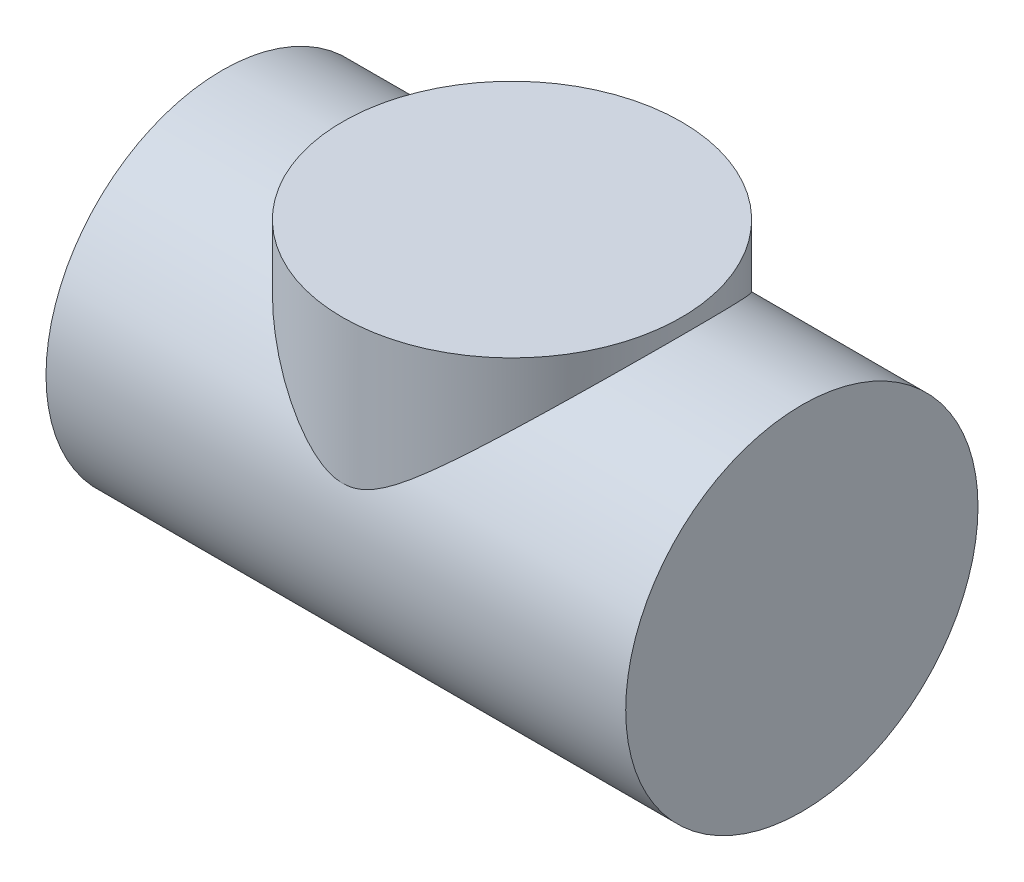
SolidWorks part; units mm, degrees
ref_plane "Front Plane" through (0, 0, 0) normal (0, 0, 1) x (1, 0, 0)
ref_plane "Top Plane" through (0, 0, 0) normal (0, 1, 0) x (1, 0, 0)
ref_plane "Right Plane" through (0, 0, 0) normal (1, 0, 0) x (0, 0, -1)
sketch "Sketch1" plane through (0, 0, 0) normal (1, 0, 0) x (0, 0, -1)
  circle A0 centre (0, 0) radius 0.0395
extrude "Boss-Extrude1" add sketch "Sketch1" along normal blind 0.13 from offset 0.065 offset against normal yes
sketch "Sketch2" plane through (0, 0, 0) normal (0, 1, 0) x (1, 0, 0)
  circle A0 centre (0, 0) radius 0.038
extrude "Boss-Extrude2" add sketch "Sketch2" along normal blind 0.043
